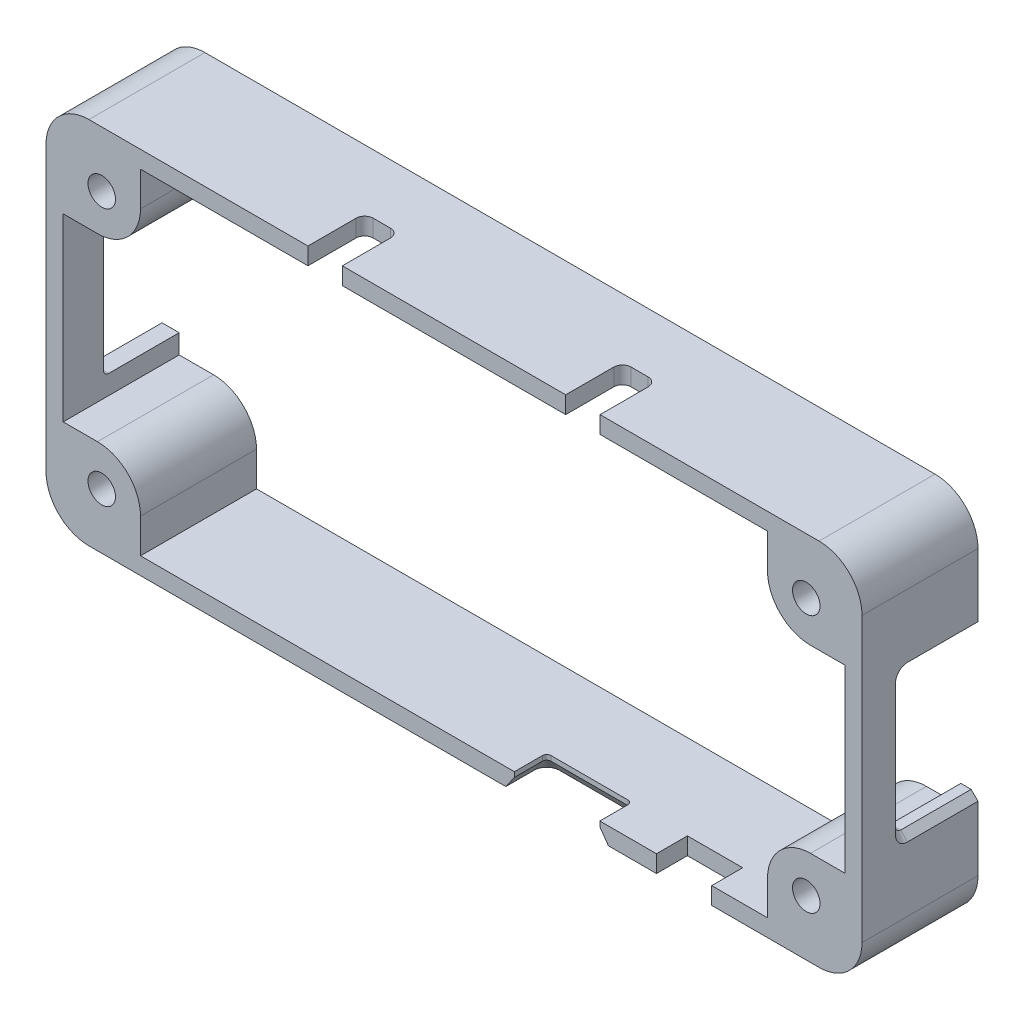
SolidWorks part; units mm, degrees
ref_plane "前视基准面" through (0, 0, 0) normal (0, 0, 1) x (1, 0, 0)
ref_plane "上视基准面" through (0, 0, 0) normal (0, 1, 0) x (1, 0, 0)
ref_plane "右视基准面" through (0, 0, 0) normal (1, 0, 0) x (0, 0, -1)
other "Configuration Table"
sketch "草图1" plane through (0, 0, 1.6001) normal (0, 0, 1) x (1, 0, 0)
  line L0 (2, -0.0127) -> (88.0002, -0.0127) construction
  line L1 (-0.4873, 0.4873) -> (90.4875, 0.4873)
  line L2 (-0.4873, 0.4873) -> (-0.4873, -38.4874)
  line L3 (-0.4873, -38.4874) -> (90.4875, -38.4874)
  line L4 (90.4875, 0.4873) -> (90.4875, -38.4874)
  line L5 (0.0127, -36.0001) -> (0.0127, -2) construction
  line L6 (89.9875, -2) -> (89.9875, -36.0001) construction
  line L7 (88.0002, -37.9874) -> (2, -37.9874) construction
  line L9 (-2.4873, 2.4873) -> (92.4875, 2.4873)
  line L10 (-2.4873, 2.4873) -> (-2.4873, -40.4874)
  line L11 (-2.4873, -40.4874) -> (92.4875, -40.4874)
  line L12 (92.4875, 2.4873) -> (92.4875, -40.4874)
  dimension "D1" = 0.5
  dimension "D2" = 0.5
  dimension "D3" = 0.5
  dimension "D4" = 0.5
  dimension "D5" = 2
  dimension "D6" = 2
  dimension "D7" = 2
  dimension "D8" = 2
extrude "凸台-拉伸1" add sketch "草图1" along normal blind 13.5
sketch "草图2" plane through (0, 0, 1.6001) normal (0, 0, 1) x (1, 0, 0)
  line L0 (90.4875, 0.4873) -> (-0.4873, 0.4873) construction
  line L1 (-0.4873, 0.4873) -> (8.5127, 0.4873)
  line L2 (-0.4873, 0.4873) -> (-0.4873, -8.5127)
  line L3 (-0.4873, -8.5127) -> (8.5127, -8.5127)
  line L4 (8.5127, 0.4873) -> (8.5127, -8.5127)
  line L6 (90.4875, 0.4873) -> (81.4875, 0.4873)
  line L7 (90.4875, 0.4873) -> (90.4875, -8.5127)
  line L8 (90.4875, -8.5127) -> (81.4875, -8.5127)
  line L9 (81.4875, 0.4873) -> (81.4875, -8.5127)
  line L10 (-0.4873, -38.4874) -> (8.5127, -38.4874)
  line L11 (-0.4873, -38.4874) -> (-0.4873, -29.4874)
  line L12 (-0.4873, -29.4874) -> (8.5127, -29.4874)
  line L13 (8.5127, -38.4874) -> (8.5127, -29.4874)
  line L14 (90.4875, -38.4874) -> (81.4875, -38.4874)
  line L15 (90.4875, -38.4874) -> (90.4875, -29.4874)
  line L16 (90.4875, -29.4874) -> (81.4875, -29.4874)
  line L17 (81.4875, -38.4874) -> (81.4875, -29.4874)
  dimension "D1" = 9
  dimension "D2" = 9
  dimension "D3" = 9
  dimension "D4" = 9
extrude "凸台-拉伸2" add sketch "草图2" along normal blind 13.5
sketch "草图3" plane through (0, 0, 1.6001) normal (0, 0, 1) x (1, 0, 0)
  circle A0 centre (4, -4) radius 1.6
  circle A1 centre (86.0002, -4) radius 1.6
  circle A2 centre (86.0002, -34.0001) radius 1.6
  circle A3 centre (4, -34.0001) radius 1.6
  dimension "D1" = 3.2
extrude "切除-拉伸1" cut sketch "草图3" along normal blind 13.5
sketch "草图4" plane through (0, 0, 1.6001) normal (0, 0, 1) x (1, 0, 0)
  line L1 (-2.4873, -10.75) -> (-0.4873, -10.75)
  line L2 (-2.4873, -10.75) -> (-2.4873, -27.25)
  line L3 (-2.4873, -27.25) -> (-0.4873, -27.25)
  line L4 (-0.4873, -10.75) -> (-0.4873, -27.25)
  line L5 (-2.4873, 2.4873) -> (-2.4873, -40.4874) construction
  line L6 (-0.4873, -8.5127) -> (-0.4873, -29.4874) construction
  line L7 (-5.15, -11.25) -> (4.5, -11.25) construction
  line L8 (90.4875, -29.4874) -> (90.4875, -8.5127) construction
  line L9 (90.4875, -10.6891) -> (92.4875, -10.6891)
  line L10 (90.4875, -10.6891) -> (90.4875, -27.1891)
  line L11 (90.4875, -27.1891) -> (92.4875, -27.1891)
  line L12 (92.4875, -10.6891) -> (92.4875, -27.1891)
  line L13 (92.4875, -40.4874) -> (92.4875, 2.4873) construction
  line L16 (87.2711, -26.6891) -> (82.7211, -26.6891) construction
  line L18 (4.5, -26.75) -> (-5.15, -26.75) construction
  line L19 (82.7211, -11.1891) -> (87.2711, -11.1891) construction
  dimension "D1" = 0.5
  dimension "D2" = 0.5
  dimension "D3" = 0.5
  dimension "D4" = 0.5
extrude "切除-拉伸2" cut sketch "草图4" along normal blind 8.8
fillet "圆角1" radius 5 4 edges at (81.4875, -29.4874, 8.3501) (8.5127, -29.4874, 8.3501) (81.4875, -8.5127, 8.3501) (8.5127, -8.5127, 8.3501)
fillet "圆角2" radius 0.6 4 edges at (91.4875, -27.1891, 10.4001) (91.4875, -10.6891, 10.4001) (-1.4873, -27.25, 10.4001) (-1.4873, -10.75, 10.4001)
sketch "草图5" plane through (0, 2.4873, 0) normal (0, 1, 0) x (1, 0, 0)
  line L0 (92.4875, -15.1001) -> (-2.4873, -15.1001) construction
  line L1 (28.0001, -15.1001) -> (32.0001, -15.1001)
  line L2 (28.0001, -15.1001) -> (28.0001, -8.5001)
  line L3 (28.0001, -8.5001) -> (32.0001, -8.5001)
  line L4 (32.0001, -15.1001) -> (32.0001, -8.5001)
  line L7 (58.0001, -15.1001) -> (62.0001, -15.1001)
  line L8 (58.0001, -15.1001) -> (58.0001, -8.5001)
  line L9 (58.0001, -8.5001) -> (62.0001, -8.5001)
  line L10 (62.0001, -15.1001) -> (62.0001, -8.5001)
  arc A0 (30.0001, -12.3001) -> (30.0001, -8.7001) centre (30.0001, -10.5001) ccw construction
  arc A1 (30.0001, -8.7001) -> (30.0001, -12.3001) centre (30.0001, -10.5001) ccw construction
  arc A2 (60.0001, -8.7001) -> (60.0001, -12.3001) centre (60.0001, -10.5001) ccw construction
  arc A3 (60.0001, -12.3001) -> (60.0001, -8.7001) centre (60.0001, -10.5001) ccw construction
  dimension "D1" = 2
  dimension "D2" = 2
  dimension "D4" = 2
  dimension "D6" = 2
  dimension "D3" = 2
  dimension "D5" = 2
extrude "切除-拉伸3" cut sketch "草图5" against normal blind 2
fillet "圆角3" radius 1 4 edges at (62.0001, 1.4873, 8.5001) (58.0001, 1.4873, 8.5001) (28.0001, 1.4873, 8.5001) (32.0001, 1.4873, 8.5001)
sketch "草图6" plane through (0, -40.4874, 0) normal (0, -1, 0) x (1, 0, 0)
  line L0 (-2.4873, 15.1001) -> (92.4875, 15.1001) construction
  line L1 (68.5664, 15.1001) -> (74.9952, 15.1001)
  line L2 (68.5664, 15.1001) -> (68.5664, 11.5001)
  line L3 (68.5664, 11.5001) -> (74.9952, 11.5001)
  line L4 (74.9952, 15.1001) -> (74.9952, 11.5001)
  line L5 (74.4952, 13.2101) -> (74.4952, 11.9101) construction
  line L6 (69.0664, 11.8107) -> (69.0664, 13.7262) construction
  line L8 (52.0301, 15.1001) -> (61.9701, 15.1001)
  line L9 (52.0301, 15.1001) -> (52.0301, 11.3401)
  line L10 (52.0301, 11.3401) -> (61.9701, 11.3401)
  line L11 (61.9701, 15.1001) -> (61.9701, 11.3401)
  line L12 (52.5301, 13.7501) -> (52.5301, 13.0901) construction
  line L13 (53.7801, 11.8401) -> (60.2201, 11.8401) construction
  line L14 (61.4701, 13.7501) -> (61.4701, 13.0901) construction
  dimension "D1" = 3.6
  dimension "D2" = 0.5
  dimension "D3" = 0.5
  dimension "D4" = 0.5
  dimension "D5" = 0.5
  dimension "D6" = 0.5
extrude "切除-拉伸4" cut sketch "草图6" against normal blind 2
fillet "圆角4" radius 0.5 2 edges at (52.0301, -39.4874, 11.3401) (61.9701, -39.4874, 11.3401)
chamfer "倒角1" distance 1 angle 55 5 edges at (61.9701, -40.4874, 13.4701) (61.8237, -40.4874, 11.4865) (57.0001, -40.4874, 11.3401) (52.1766, -40.4874, 11.4865) (52.0301, -40.4874, 13.4701)
fillet "圆角5" radius 5 4 edges at (92.4875, -40.4874, 8.3501) (92.4875, 2.4873, 8.3501) (-2.4873, 2.4873, 8.3501) (-2.4873, -40.4874, 8.3501)
chamfer "倒角2" distance 0.8 angle 45 5 edges at (92.4875, -27.1891, 5.7001) (92.4875, -27.0133, 10.2243) (92.4875, -18.9391, 10.4001) (92.4875, -10.8648, 10.2243) (92.4875, -10.6891, 5.7001)
